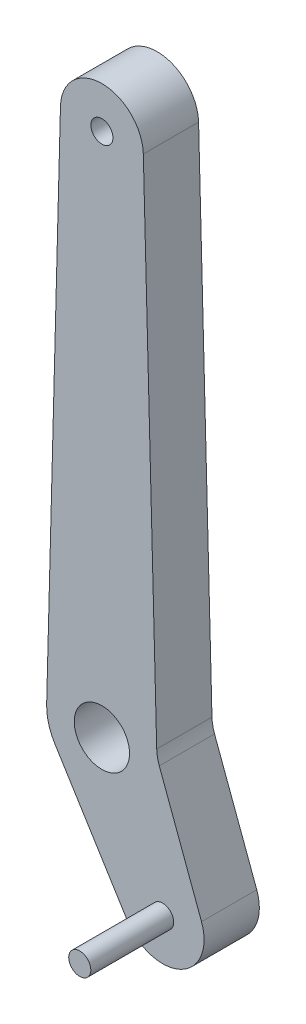
SolidWorks part; units mm, degrees
ref_plane "前视基准面" through (0, 0, 0) normal (0, 0, 1) x (1, 0, 0)
ref_plane "上视基准面" through (0, 0, 0) normal (0, 1, 0) x (1, 0, 0)
ref_plane "右视基准面" through (0, 0, 0) normal (1, 0, 0) x (0, 0, -1)
other "Configuration Table"
sketch "草图1" plane through (0, 0, 0) normal (0, 0, 1) x (1, 0, 0)
  line L0 (0, 0) -> (21.9891, -44.9052) construction
  line L1 (-14.9948, 190.3947) -> (-19.9931, 0.5263)
  line L2 (14.9948, 190.3947) -> (19.8402, 6.332)
  line L3 (-16.9925, -10.5478) -> (9.2448, -52.816)
  line L4 (36.0528, -39.6887) -> (20.7713, 1.5102)
  arc A0 (-19.9931, 0.5263) -> (-16.9925, -10.5478) centre (0, 0) ccw
  arc A1 (14.9948, 190.3947) -> (-14.9948, 190.3947) centre (0, 190) ccw
  arc A2 (9.2448, -52.816) -> (36.0528, -39.6887) centre (21.9891, -44.9052) ccw
  arc A3 (20.7713, 1.5102) -> (19.8402, 6.332) centre (34.835, 6.7267) cw
  circle A4 centre (0, 190) radius 4
  circle A5 centre (0, 0) radius 10
  dimension "D1" = 15
extrude "凸台-拉伸1" add sketch "草图1" along normal blind 20
sketch "草图2" plane through (0, 0, 20) normal (0, 0, 1) x (1, 0, 0)
  circle A0 centre (21.9891, -44.9052) radius 4
extrude "凸台-拉伸2" add sketch "草图2" along normal blind 30
